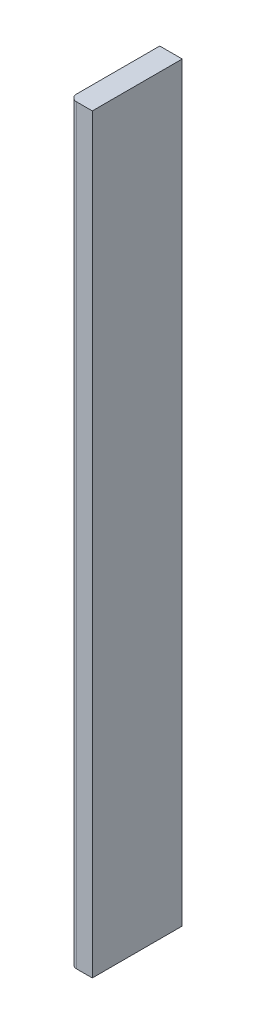
SolidWorks part; units mm, degrees
ref_plane "Спереди" through (0, 0, 0) normal (0, 0, 1) x (1, 0, 0)
ref_plane "Сверху" through (0, 0, 0) normal (0, 1, 0) x (1, 0, 0)
ref_plane "Справа" through (0, 0, 0) normal (1, 0, 0) x (0, 0, -1)
sketch "Эскиз1" plane through (-0.1, 0, 0) normal (-1, 0, 0) x (0, 0, 1)
  line L0 (4, -16.7) -> (0, -16.7)
  line L1 (0, -16.9) -> (0, 16.9) construction
  line L2 (-6, -16.7) -> (4, -16.7) construction
  line L3 (0, -16.7) -> (0, 16.7)
  line L4 (4, 16.7) -> (-6, 16.7) construction
  line L5 (0, 16.7) -> (4, 16.7)
  line L6 (4, 16.7) -> (4, -16.7)
extrude "Бобышка-Вытянуть1" add sketch "Эскиз1" along normal blind 1
fillet "Скругление1" radius 0.3 1 edges at (-1.1, 0, 4)
